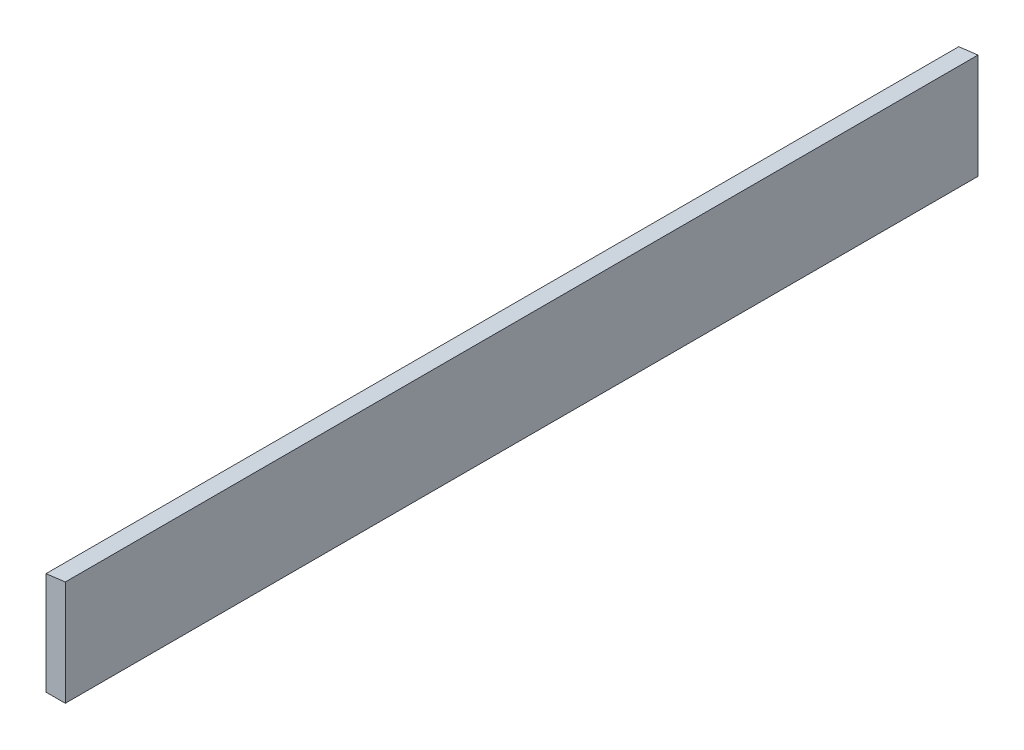
SolidWorks part; units mm, degrees
material "Pine"
ref_plane "Front Plane" through (0, 0, 0) normal (0, 0, 1) x (1, 0, 0)
ref_plane "Top Plane" through (0, 0, 0) normal (0, 1, 0) x (1, 0, 0)
ref_plane "Right Plane" through (0, 0, 0) normal (1, 0, 0) x (0, 0, -1)
sketch "Sketch1" plane through (0, 0, 0) normal (0, 0, 1) x (1, 0, 0)
  line L0 (232.7863, 27.1947) -> (486.7863, 27.1947)
  line L1 (486.7863, 27.1947) -> (486.7863, 179.5947)
  line L2 (486.7863, 179.5947) -> (79.2003, 128.6129)
  line L3 (232.7863, 128.6253) -> (232.7863, 27.1947)
  line L4 (486.7863, 160.3962) -> (81.5647, 109.7102)
  line L5 (251.8363, 131.0081) -> (251.8363, 27.1947)
  line L6 (467.7363, 158.0134) -> (251.8363, 131.0081) construction
  line L7 (467.7363, 27.1947) -> (467.7363, 158.0134)
  line L8 (251.8363, 46.2447) -> (467.7363, 46.2447) construction
  line L9 (251.8363, 131.0081) -> (251.8363, 46.2447) construction
  line L10 (467.7363, 46.2447) -> (467.7363, 158.0134) construction
  line L11 (486.7863, 160.3962) -> (484.4219, 179.2989)
  line L12 (486.7863, 27.1947) -> (486.7863, 179.5947) construction
  line L13 (486.7863, 179.5947) -> (232.7863, 147.8238) construction
  line L14 (81.5647, 109.7102) -> (60.2851, 279.8345) construction
  line L15 (232.7863, 147.8238) -> (232.7863, 27.1947) construction
  line L16 (81.5647, 109.7102) -> (79.2003, 128.6129)
  line L17 (484.4219, 179.2989) -> (230.4219, 147.528) construction
  line L22 (616.7284, 349.4357) -> (60.2851, 279.8345) construction
  line L23 (638.0079, 179.3114) -> (616.7284, 349.4357) construction
  line L24 (232.7863, 128.6253) -> (230.4219, 147.528) construction
  line L25 (232.7863, 27.1947) -> (486.7863, 27.1947) construction
  dimension "D1" = 97.13
extrude "Boss-Extrude1" add sketch "Sketch1" along normal blind 901.7 contours L5 L4 L3 L0
